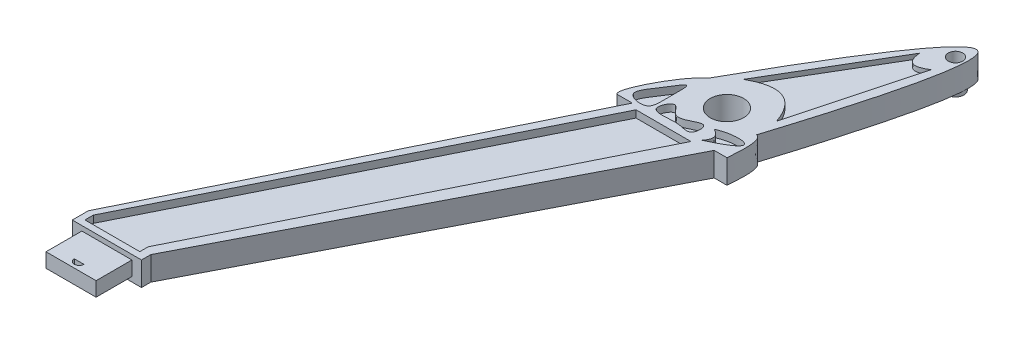
SolidWorks part; units mm, degrees
ref_plane "前视基准面" through (0, 0, 0) normal (0, 0, 1) x (1, 0, 0)
ref_plane "上视基准面" through (0, 0, 0) normal (0, 1, 0) x (1, 0, 0)
ref_plane "右视基准面" through (0, 0, 0) normal (1, 0, 0) x (0, 0, -1)
other "Configuration Table"
sketch "草图1" plane through (0, 0, 0) normal (0, 1, 0) x (1, 0, 0)
  line L0 (0, 0) -> (-74.7574, -152.8307)
  line L1 (0, 0) -> (34.2819, 0)
  line L2 (34.2819, 0) -> (-45.8091, -155.597)
  line L7 (-6.4129, 0) -> (39.6216, 0)
  line L8 (-45.8091, -155.597) -> (-45.8091, -159.4941)
  line L9 (-74.7574, -152.8307) -> (-74.7574, -159.4941)
  line L10 (-74.7574, -159.4941) -> (-45.8091, -159.4941)
  circle A3 centre (50.9438, 84.2657) radius 3
  circle A4 centre (21.6232, 17.9784) radius 7
  spline S0 degree 3 poles (-6.4129, 0) (-9.5664, 2.1245) (13.1676, 41.5699) (6.7363, 5.6298) (31.3832, 7.6373) (41.687, 23.5447) (39.6216, 0) knots 0 0 0 0 0.340385 0.521253 0.667113 1 1 1 1
  spline S1 degree 2 poles (6.8533, 24.8458) (83.9483, 162.9436) (37.4975, 14.5144) knots 0 0 0 1 1 1
extrude "凸台-拉伸2" add sketch "草图1" along normal blind 10
ref_plane "基准面2" through (0, 10, 0) normal (0, 1, 0) x (1, 0, 0)
sketch "草图2" plane through (0, 10, 0) normal (0, 1, 0) x (1, 0, 0)
  spline S0 degree 3 poles (5.0863, 9.3527) (6.0553, 21.6376) (0.0737, 10.5706) (-6.1634, 2.6775) (6.3091, 0.1581) (5.0863, 9.3527) (6.0553, 21.6376) (0.0737, 10.5706) knots -0.576889 -0.407216 -0.197275 0 0.210594 0.423111 0.592784 0.802725 1 1.210594 1.423111 1.592784 only from (4.9648, 17.7733) to (4.9648, 17.7733)
  spline S1 degree 3 poles (4.9097, 1.9569) (9.5376, 11.4465) (13.9274, 0.3253) (24.186, 11.1866) (23.8667, 0.1377) (17.0017, 2.5454) (12.7448, 1.7004) (4.9097, 1.9569) (9.5376, 11.4465) (13.9274, 0.3253) knots -0.405345 -0.24577 -0.134016 0 0.134824 0.368002 0.480861 0.594655 0.75423 0.865984 1 1.134824 1.368002 1.480861 only from (9.2996, 8.2807) to (9.2996, 8.2807)
  spline S2 degree 2 poles (26.6936, 7.6222) (31.575, 5.1094) (27.9007, 1.0377) knots 0 0 0 1 1 1
  spline S3 degree 3 poles (26.6936, 7.6222) (32.2309, 10.7448) (49.593, 10.7946) (27.9007, 1.0377) knots 0 0 0 0 1 1 1 1
extrude "切除-拉伸1" cut sketch "草图2" against normal blind 3
ref_plane "基准面4" through (0, 5, 0) normal (0, 1, 0) x (1, 0, 0)
mirror "镜向1" about plane through (0, 5, 0) normal (0, 1, 0) of "切除-拉伸1"
sketch "草图12" plane through (0, 10, 0) normal (0, 1, 0) x (1, 0, 0)
  line L0 (3.2209, -1.6547) -> (26.1782, -1.6547)
  line L1 (26.1782, -1.6547) -> (-49.1832, -153.3257)
  line L3 (-72.1406, -153.3257) -> (3.2209, -1.6547)
  line L4 (-49.1832, -153.3257) -> (-49.1832, -156.8257)
  line L5 (-72.1406, -153.3257) -> (-72.1406, -156.8257)
  line L6 (-72.1406, -156.8257) -> (-49.1832, -156.8257)
extrude "切除-拉伸3" cut sketch "草图12" against normal blind 3
ref_plane "基准面5" through (0, 5, 0) normal (0, 1, 0) x (1, 0, 0)
mirror "镜向2" about plane through (0, 5, 0) normal (0, 1, 0) of "切除-拉伸3"
ref_plane "基准面6" through (0, 0, 159.4941) normal (0, 0, 1) x (1, 0, 0)
sketch "草图13" plane through (0, 0, 159.4941) normal (0, 0, 1) x (1, 0, 0)
  line L0 (-70.7574, 8) -> (-70.7574, 2)
  line L1 (-70.7574, 2) -> (-49.8091, 2)
  line L2 (-74.7574, 10) -> (-74.7574, 0) construction
  line L3 (-74.7574, 0) -> (-45.8091, 0) construction
  line L4 (-49.8091, 2) -> (-49.8091, 8)
  line L5 (-49.8091, 8) -> (-70.7574, 8)
  line L6 (-45.8091, 10) -> (-45.8091, 0) construction
  line L7 (-74.7574, 10) -> (-45.8091, 10) construction
  dimension "D1" = 4
  dimension "D2" = 2
  dimension "D3" = 4
  dimension "D4" = 2
extrude "凸台-拉伸3" add sketch "草图13" along normal blind 15
sketch "草图16" plane through (0, 8, 0) normal (0, 1, 0) x (1, 0, 0)
  line L1 (-62.2833, -171.1179) -> (-58.2833, -171.1179)
  arc A0 (-62.2833, -171.1179) -> (-58.2833, -171.1179) centre (-60.2833, -171.1179) ccw
extrude "切除-拉伸4" cut sketch "草图16" against normal blind 6
sketch "草图17" plane through (0, 10, 0) normal (0, 1, 0) x (1, 0, 0)
  line L0 (42.0269, 78.1872) -> (14.653, 31.8192)
  line L1 (50.4066, 74.6119) -> (36.7755, 23.5512)
  spline S0 degree 2 poles (42.0269, 78.1872) (42.7408, 69.5836) (50.4066, 74.6119) knots 0 0 0 1 1 1
  spline S1 degree 2 poles (14.653, 31.8192) (30.7572, 40.9486) (36.7755, 23.5512) knots 0 0 0 1 1 1
extrude "切除-拉伸5" cut sketch "草图17" against normal blind 2
mirror "镜向3" about plane through (0, 5, 0) normal (0, 1, 0) of "切除-拉伸5"
sketch "草图18" plane through (0, 0, 0) normal (0, -1, 0) x (1, 0, 0)
  circle A0 centre (50.9438, -84.2657) radius 3
sketch "草图20" plane through (0, 0, 0) normal (0, -1, 0) x (1, 0, 0)
  circle A0 centre (50.9438, -84.2657) radius 3
  circle A1 centre (50.9438, -84.2657) radius 3.5
extrude "凸台-拉伸5" add sketch "草图20" along normal blind 2
